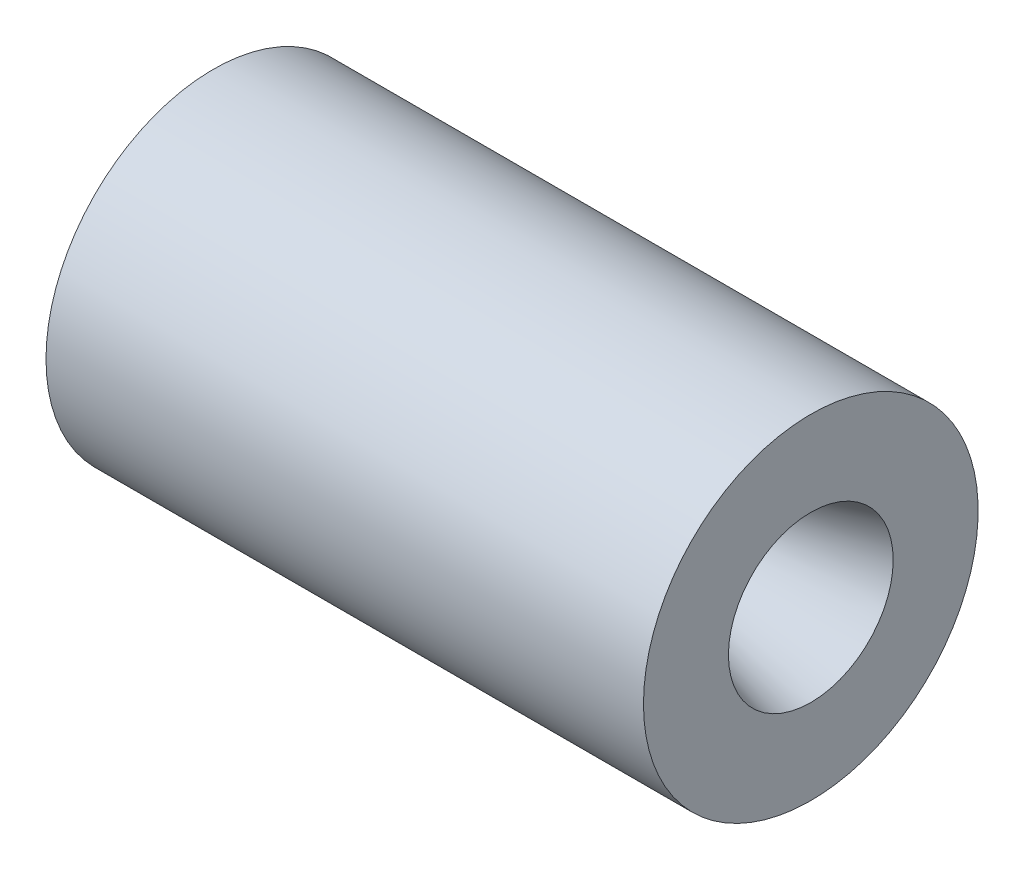
SolidWorks part; units mm, degrees
ref_plane "Front Plane" through (0, 0, 0) normal (0, 0, 1) x (1, 0, 0)
ref_plane "Top Plane" through (0, 0, 0) normal (0, 1, 0) x (1, 0, 0)
ref_plane "Right Plane" through (0, 0, 0) normal (1, 0, 0) x (0, 0, -1)
sketch "Model" plane through (0, 0, 0) normal (0, 0, 1) x (1, 0, 0)
  line L0 (0, 47.5732) -> (117.4744, 47.5732)
  line L1 (127.6903, 44.8359) -> (170.3612, 20.1998)
  line L2 (184.6389, 17.0386) -> (249.3839, 34.387)
  line L3 (0, 0) -> (249.3839, 0) construction
  line L4 (0, 47.5732) -> (0, 69.85)
  line L5 (0, 69.85) -> (249.3839, 69.85)
  line L6 (249.3839, 69.85) -> (249.3839, 34.387)
  arc A0 (127.6903, 44.8359) -> (117.4744, 47.5732) centre (117.4744, 27.1414) ccw
  arc A1 (170.3612, 20.1998) -> (182.976, 16.8197) centre (182.976, 42.0492) ccw
  arc A2 (182.976, 16.8197) -> (184.6389, 17.0386) centre (182.976, 23.2448) ccw
  dimension "D1" = 47.5732
  dimension "D2" = 69.85
  dimension "D3" = 249.3839
revolve "Revolve1" add sketch "Model" angle 360 about L3
